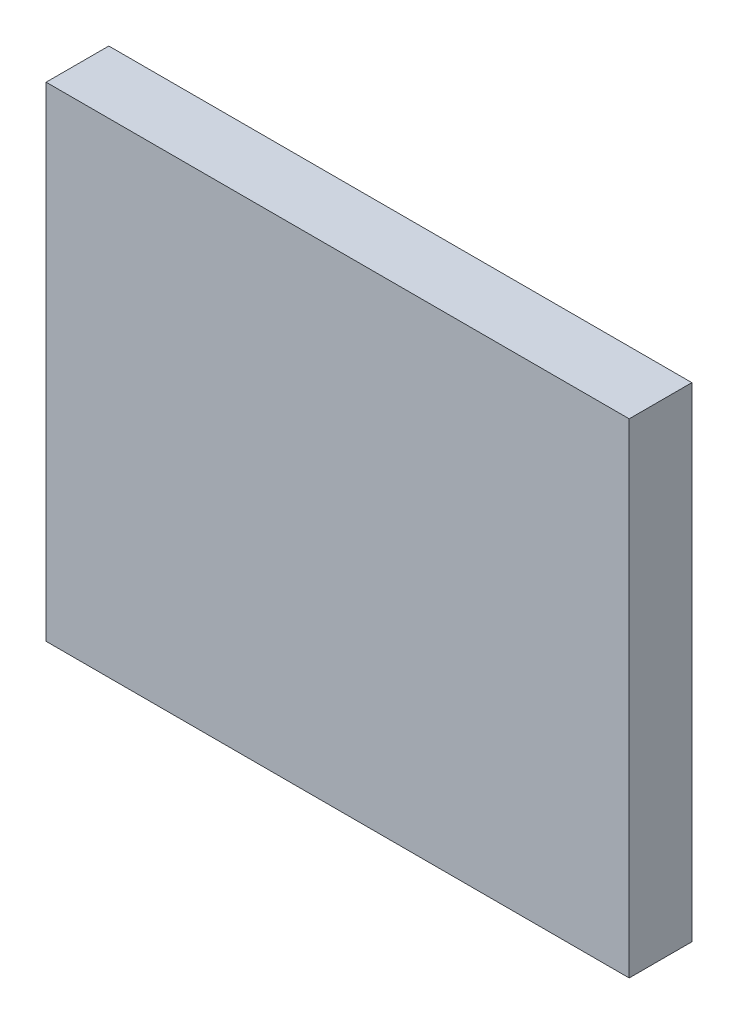
SolidWorks part; units mm, degrees
ref_plane "Спереди" through (0, 0, 0) normal (0, 0, 1) x (1, 0, 0)
ref_plane "Сверху" through (0, 0, 0) normal (0, 1, 0) x (1, 0, 0)
ref_plane "Справа" through (0, 0, 0) normal (1, 0, 0) x (0, 0, -1)
sketch "Эскиз1_fr" plane through (0, 0, 0) normal (0, 0, 1) x (1, 0, 0)
  line L1 (-48.994, 38.0205) -> (44.0482, 38.0205)
  line L2 (-48.994, 38.0205) -> (-48.994, -39.257)
  line L3 (-48.994, -39.257) -> (44.0482, -39.257)
  line L4 (44.0482, 38.0205) -> (44.0482, -39.257)
extrude "Бобышка-Вытянуть1" add sketch "Эскиз1_fr" along normal blind 10
sketch "Эскиз4" plane through (0, 0, 0) normal (0, 1, 0) x (1, 0, 0)
  line L0 (-48.994, 0) -> (44.0482, 0) construction
  point P0 (0, 7)
  dimension "D1" = 7
ref_plane "Плоскость3" through (0, 0, -7) normal (0, 0, 1) x (1, 0, 0)
